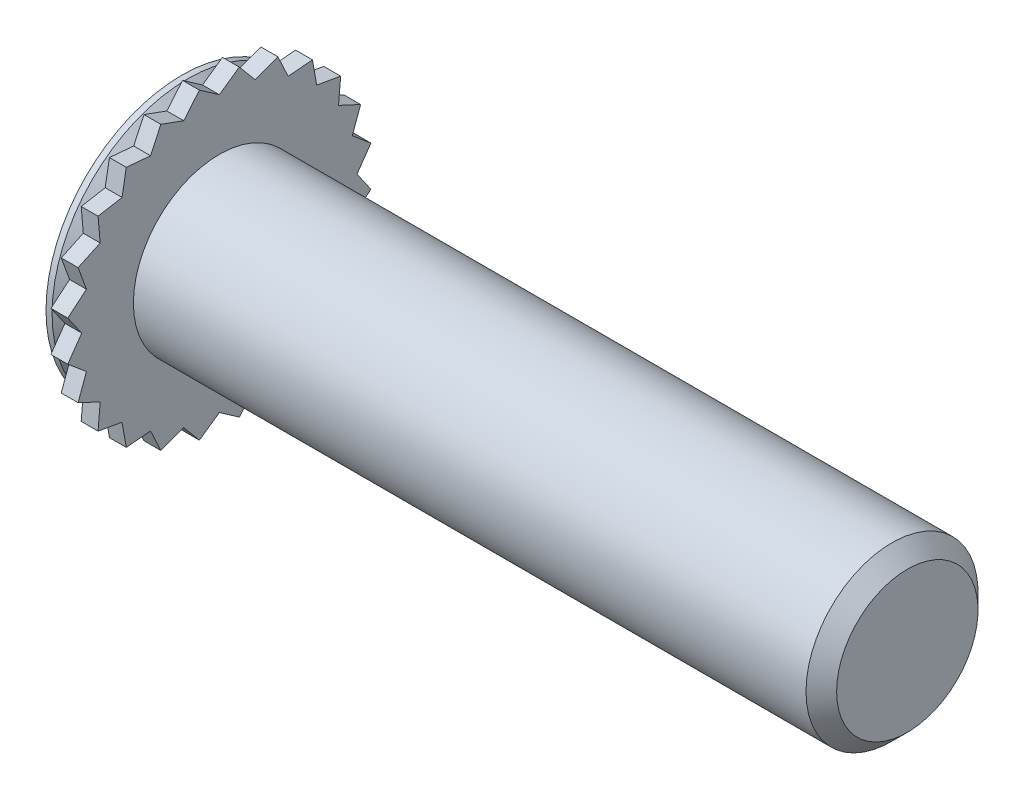
SolidWorks part; units mm, degrees
revolve "BaseBody" add sketch "BodySke" angle 360 about L6
sketch "BodySke" plane through (0, 0, 0) normal (0, 0, 1) x (1, 0, 0)
  line L0 (0, 2.2225) -> (0, 3.95)
  line L1 (1.09, 4.445) -> (0.5995, 4.445)
  line L2 (0.5995, 4.445) -> (0.5995, 3.6373)
  line L3 (1.09, 2.5) -> (20.645, 2.5)
  line L4 (21.09, 2.055) -> (21.09, 0)
  line L5 (21.09, 0) -> (0.545, 0)
  line L6 (0, 0) -> (50.554, 0) construction
  line L7 (1.09, 4.445) -> (1.09, 2.5)
  line L8 (21.09, 2.055) -> (20.645, 2.5)
  line L9 (0.5995, 3.6373) -> (0.4905, 3.6373)
  line L10 (0.4905, 3.6373) -> (0.1778, 3.95)
  line L11 (1.89, 19.05) -> (1.89, -3.175) construction
  line L12 (0.1778, 3.95) -> (0, 3.95)
  line L13 (0, 2.2225) -> (0.545, 1.6775)
  line L14 (0.545, 1.6775) -> (0.545, 0)
  dimension "Body_ch_ang" = 45
  dimension "Advance" = 0.8
  dimension "Minor_dia" = 4.11
  dimension "Diameter" = 5
  dimension "Length" = 20
  dimension "A_dim" = 1.09
  dimension "Clinch_ht" = 0.4905
  dimension "E_dia" = 8.89
  dimension "C_dia" = 7.9
  dimension "C_len" = 0.1778
  dimension "Skirt_ht" = 0.4905
  dimension "D1" = 45
  dimension "Face_clr_dep" = 0.545
  dimension "Face_clr_dia" = 4.445
  dimension "Face_clr_ang" = 45
cosmetic thread "ThreadCosmetic" [suppressed] parameters "Thread_length"=18.4, "Thread_minor"=4.11
ref_plane "Plane1" through (0, 0, 0) normal (0, 0, 1) x (1, 0, 0)
ref_plane "Plane2" through (0, 0, 0) normal (0, 1, 0) x (1, 0, 0)
ref_plane "Plane3" through (0, 0, 0) normal (1, 0, 0) x (0, 0, -1)
sketch "ThdSchSke" plane through (0, 0, 0) normal (0, 0, 1) x (1, 0, 0)
  line L0 (2.69, -2.055) -> (2.3784, -2.5)
  line L1 (2.69, -2.055) -> (3.0016, -2.5)
  line L2 (3.0016, -2.5) -> (3.0016, -3.125)
  line L3 (-3.175, 0) -> (5.1513, 0) construction
  line L5 (3.0016, -3.125) -> (2.3784, -3.125)
  line L6 (2.3784, -3.125) -> (2.3784, -2.5)
  line L8 (1.09, -2.5) -> (1.09, 2.5) construction
  dimension "Diameter" = 5
  dimension "SideAngle" = 55
  dimension "VeeAngle" = 70
  dimension "Thread_minor" = 4.11
  dimension "Overcut" = 6.25
  dimension "Start" = 1.6
revolve "ThreadSchematic" [suppressed] cut sketch "ThdSchSke" angle 360 about L3
pattern_linear "ThdSchPat" [suppressed]
sketch "CliRinCutSke" plane through (1.09, 0, 0) normal (1, 0, 0) x (0, 0, -1)
  line L0 (0, 0) -> (0, 4.8256) construction
  line L1 (0.5802, 4.407) -> (0, 4.0005)
  line L2 (0, 4.0005) -> (-0.5802, 4.407)
  arc A0 (0.5802, 4.407) -> (-0.5802, 4.407) centre (0, 0) ccw
  circle A1 centre (0, 0) radius 4.445 construction
  circle A2 centre (0, 0) radius 4.0005 construction
  dimension "Angle" = 15
extrude "ClinchCut" cut sketch "CliRinCutSke" against normal blind 0.4905
pattern_circular "ClinchCutPat" count 24 every 15 about axis through (0, 0, 0) along (1, 0, 0) of "ClinchCut"
equation "' \"Length@BodySke\" = 20"
equation "' \"A_dim@BodySke\" = 1.09"
equation "' \"E_dia@BodySke\" = 8.89"
equation "' \"C_dia@BodySke\" = 7.9"
equation "' \"Diameter@BodySke\" = 5"
equation "' \"Minor_dia@BodySke\" = 4.11"
equation "' \"Advance@BodySke\" = 0.8"
equation "\"Face_clr_dia@BodySke\" = \"E_dia@BodySke\" / 2"
equation "\"Face_clr_dep@BodySke\" = \"A_dim@BodySke\" / 2"
equation "\"Start@ThdSchSke\" = 1.6"
equation "\"Skirt_ht@BodySke\" = \"A_dim@BodySke\" * 0.45"
equation "\"Clinch_ht@BodySke\" = \"A_dim@BodySke\" * 0.45"
equation "\"Depth@ClinchCut\" = \"A_dim@BodySke\" * 0.45"
equation "\"Count@ClinchCutPat\" = 24"
equation "\"Angle@ClinchCutPat\" = 360 / \"Count@ClinchCutPat\""
equation "\"Angle@CliRinCutSke\" = 360 / \"Count@ClinchCutPat\""
equation "\"Clinch_minor@CliRinCutSke\" =  \"C_dia@BodySke\" "
equation "\"Clinch_minor@CliRinCutSke\" =  \"E_dia@BodySke\" * 0.9"
equation "\"Thread_length@ThreadCosmetic\" = \"Length@BodySke\" - \"Start@ThdSchSke\""
equation "\"Thread_minor@ThreadCosmetic\" = \"Minor_dia@BodySke\""
equation "\"Thread_minor@ThdSchSke\" = \"Minor_dia@BodySke\""
equation "\"Diameter@ThdSchSke\" = \"Diameter@BodySke\""
equation "\"Overcut@ThdSchSke\" = \"Diameter@BodySke\" * 1.25"
equation "\"Num_threads@ThdSchPat\" = int( \"Thread_length@ThreadCosmetic\" / \"Advance@BodySke\" + 0.999 )  + 1"
equation "\"Advance@ThdSchPat\" = \"Thread_length@ThreadCosmetic\" /  (\"Num_threads@ThdSchPat\" - 1) 'relax it"
equation "\"Num_threads@ThdSchPat\" = \"Num_threads@ThdSchPat\" - sgn( \"Num_threads@ThdSchPat\" - 1) '---chamfered tips only---"
